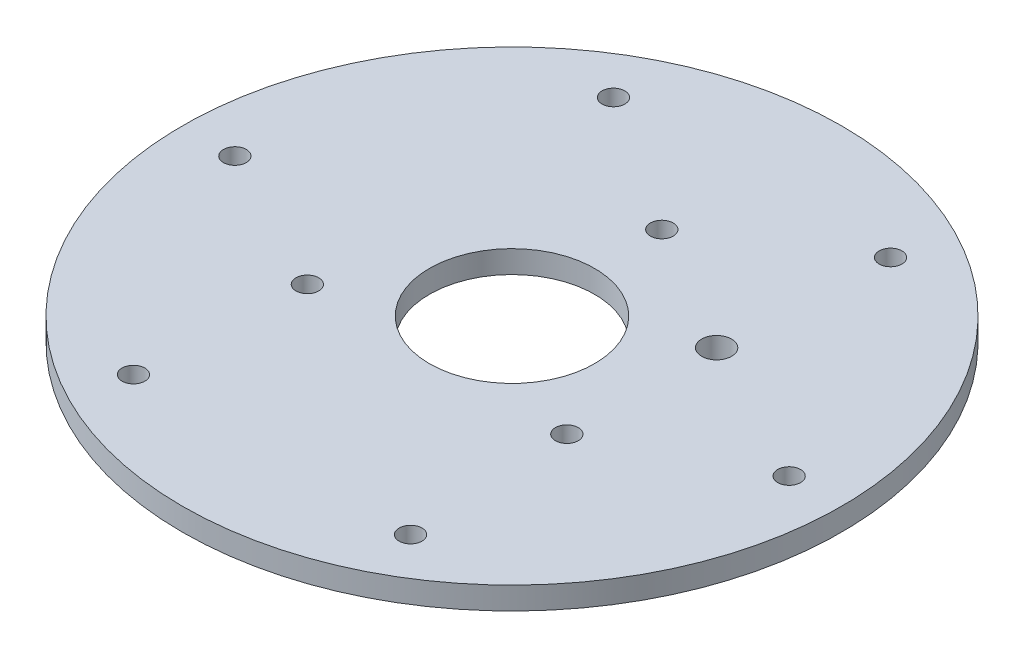
SolidWorks part; units mm, degrees
ref_plane "前视基准面" through (0, 0, 0) normal (0, 0, 1) x (1, 0, 0)
ref_plane "上视基准面" through (0, 0, 0) normal (0, 1, 0) x (1, 0, 0)
ref_plane "右视基准面" through (0, 0, 0) normal (1, 0, 0) x (0, 0, -1)
other "Configuration Table"
sketch "草图1" plane through (0, 0, 0) normal (0, 1, 0) x (1, 0, 0)
  line L0 (34, 0) -> (40, 0) construction
  line L1 (40, 0) -> (44, 0) construction
  line L2 (0, 0) -> (20, 0) construction
  line L3 (0, 0) -> (17.3205, 10) construction
  circle A0 centre (0, 0) radius 34
  circle A1 centre (0, 0) radius 44
  circle A2 centre (0, 0) radius 40 construction
  circle A3 centre (37, 0) radius 1.525
  circle A4 centre (18.5, -32.0429) radius 1.525
  circle A5 centre (-18.5, -32.0429) radius 1.525
  circle A6 centre (-37, 0) radius 1.525
  circle A7 centre (-18.5, 32.0429) radius 1.525
  circle A8 centre (18.5, 32.0429) radius 1.525
  circle A9 centre (0, 0) radius 20 construction
  circle A10 centre (0, 0) radius 11.025
  circle A11 centre (0, 20) radius 1.525
  circle A12 centre (17.3205, -10) radius 1.525
  circle A13 centre (-17.3205, -10) radius 1.525
  circle A14 centre (17.3205, 10) radius 2
  point P22 (0, 0)
  point P31 (0, 0)
  dimension "D1" = 80
  dimension "D4" = 3.05
  dimension "D6" = 22.05
  dimension "D7" = 40
  dimension "D8" = 3.05
  dimension "D11" = 4
  dimension "D2" = 6
  dimension "D3" = 4
  dimension "D10" = 30
  dimension "D5" = 6
  dimension "D9" = 3
extrude "凸台-拉伸1" add sketch "草图1" along normal blind 3 contours A0 | A1 A8 A7 A6 A5 A4 A3 A0
